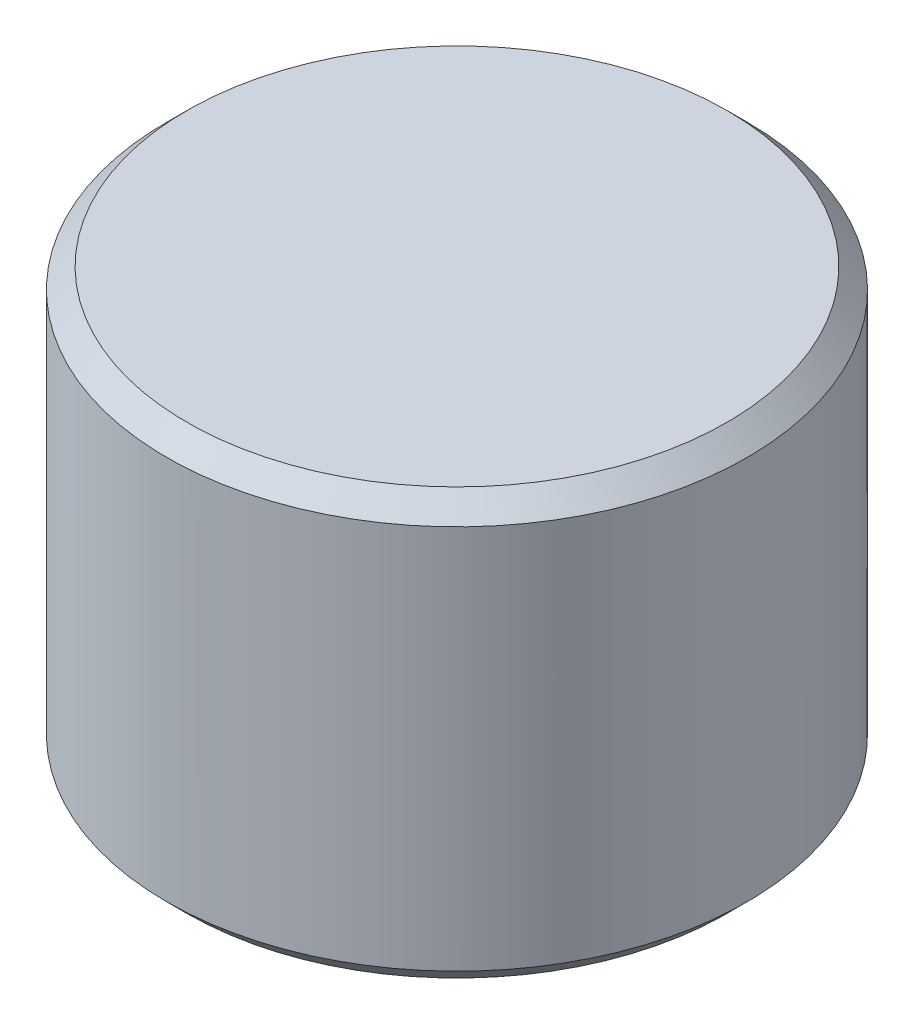
SolidWorks part; units mm, degrees
ref_plane "Front Plane" through (0, 0, 0) normal (0, 0, 1) x (1, 0, 0)
ref_plane "Top Plane" through (0, 0, 0) normal (0, 1, 0) x (1, 0, 0)
ref_plane "Right Plane" through (0, 0, 0) normal (1, 0, 0) x (0, 0, -1)
sketch "Sketch1" plane through (0, 0, 0) normal (0, 1, 0) x (1, 0, 0)
  circle A0 centre (0, 0) radius 4.3
  dimension "D1" = 8.6
extrude "Boss-Extrude1" add sketch "Sketch1" along normal blind 6.3
chamfer "Chamfer1" distance 0.3 angle 45 2 edges at (0, 0, 4.3) (0, 6.3, 4.3)
equation "\"pin_circle_R\" = 27"
equation "\"ecc\" = 1.5"
equation "\"n_pins\" = 11"
equation "\"pin_d\" = 3"
equation "\"out_pin_R\" = 18.5"
equation "\"disc_clr\" = 0.1"
equation "\"seat_6803\" = 26.1"
equation "\"disc_t\" = 5"
equation "\"out_hole_clr\" = 0.5"
equation "\"boss_17\" = 17.15"
equation "\"rotor_bolt_R\" = 10"
equation "\"m25_clr\" = 2.8"
equation "\"m25_head\" = 5"
equation "\"insert_hole\" = 4.4"
equation "\"csk\" = 0.6"
equation "\"peg_d\" = 3.0"
equation "\"plug_d\" = 8.6"
equation "\"D1@Sketch1\"=\"plug_d\""
